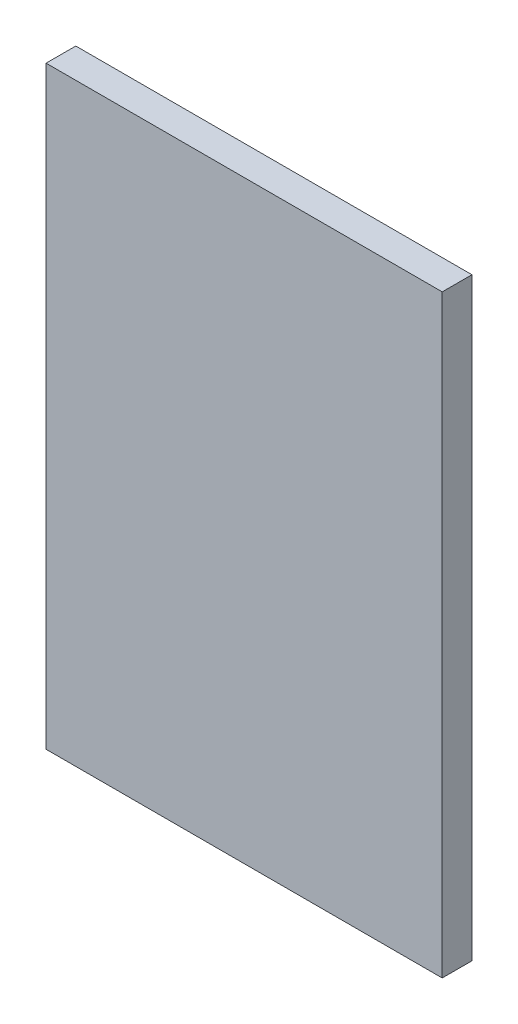
SolidWorks part; units mm, degrees
ref_plane "Front Plane" through (0, 0, 0) normal (0, 0, 1) x (1, 0, 0)
ref_plane "Top Plane" through (0, 0, 0) normal (0, 1, 0) x (1, 0, 0)
ref_plane "Right Plane" through (0, 0, 0) normal (1, 0, 0) x (0, 0, -1)
sketch "Sketch1" plane through (0, 0, 0) normal (0, 0, 1) x (1, 0, 0)
  line L0 (166.6667, 500) -> (833.3333, 500) construction
sketch "Sketch2" plane through (0, 0, 0) normal (0, 0, 1) x (1, 0, 0)
  line L0 (0, 0) -> (0, 60)
  line L1 (0, 60) -> (40, 60)
  line L2 (40, 60) -> (40, 0)
  line L3 (40, 0) -> (0, 0)
  point P2 (0, 0)
  point P5 (0, 0)
  dimension "D1" = 40
  dimension "D2" = 60
extrude "Boss-Extrude1" add sketch "Sketch2" along normal blind 3
